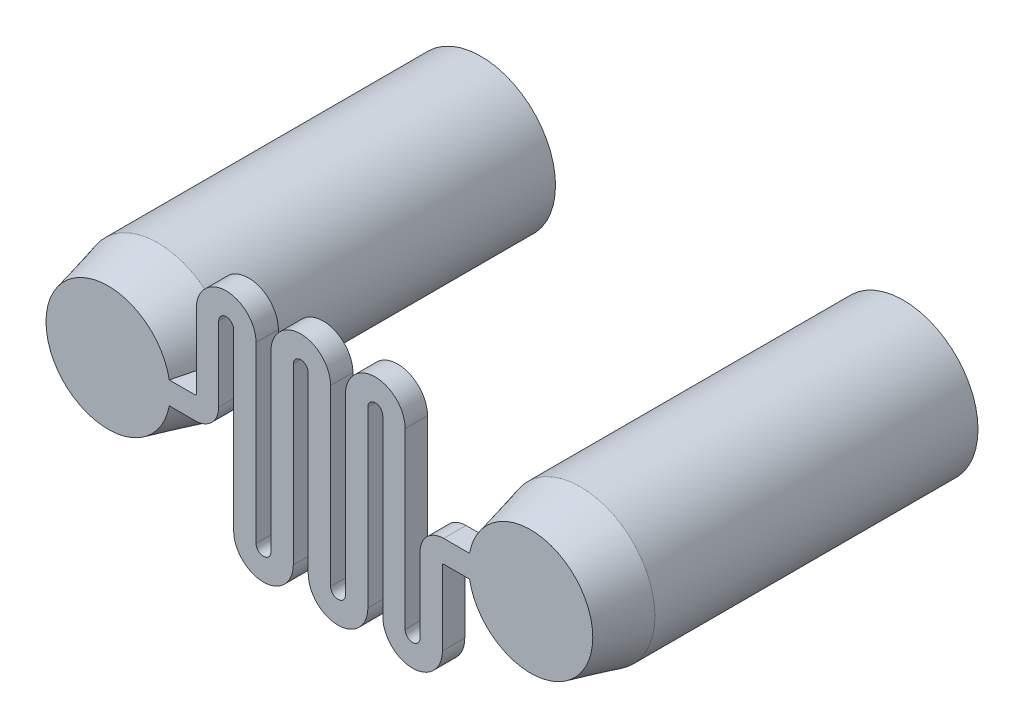
SolidWorks part; units mm, degrees
ref_plane "Front Plane" through (0, 0, 0) normal (0, 0, 1) x (1, 0, 0)
ref_plane "Top Plane" through (0, 0, 0) normal (0, 1, 0) x (1, 0, 0)
ref_plane "Right Plane" through (0, 0, 0) normal (1, 0, 0) x (0, 0, -1)
sketch "Sketch2" plane through (0, 0, 0) normal (0, 0, 1) x (1, 0, 0)
  line L3 (-20.5, -0.9) -> (-13.5, -0.9)
  line L6 (-11.6, 1) -> (-11.6, 7)
  line L9 (-10.4, 7) -> (-10.4, 0)
  line L12 (-10.4, 0) -> (-10.4, -7)
  line L15 (-5.6, -7) -> (-5.6, 0)
  line L18 (-5.6, 0) -> (-5.6, 7)
  line L21 (-4.4, 7) -> (-4.4, 0)
  line L22 (-4.4, 0) -> (-4.4, -7)
  line L23 (0.4, -7) -> (0.4, 0)
  line L24 (0.4, 0) -> (0.4, 7)
  line L25 (1.6, 7) -> (1.6, 0)
  line L26 (1.6, 0) -> (1.6, -7)
  line L27 (6.4, -7) -> (6.4, -1)
  line L28 (6.5, -0.9) -> (13.5, -0.9)
  line L29 (-20.5, 0.9) -> (-13.5, 0.9)
  line L30 (-13.4, 1) -> (-13.4, 7)
  line L31 (-8.6, 7) -> (-8.6, 0)
  line L32 (-8.6, 0) -> (-8.6, -7)
  line L33 (-7.4, -7) -> (-7.4, 0)
  line L34 (-7.4, 0) -> (-7.4, 7)
  line L35 (-2.6, 7) -> (-2.6, 0)
  line L36 (-2.6, 0) -> (-2.6, -7)
  line L37 (-1.4, -7) -> (-1.4, 0)
  line L38 (-1.4, 0) -> (-1.4, 7)
  line L39 (3.4, 7) -> (3.4, 0)
  line L40 (3.4, 0) -> (3.4, -7)
  line L41 (4.6, -7) -> (4.6, -1)
  line L42 (6.5, 0.9) -> (13.5, 0.9)
  arc A8 (-11.6, 1) -> (-13.5, -0.9) centre (-13.5, 1) cw
  arc A9 (-11.6, 7) -> (-10.4, 7) centre (-11, 7) cw
  arc A10 (-10.4, -7) -> (-5.6, -7) centre (-8, -7) ccw
  arc A11 (-5.6, 7) -> (-4.4, 7) centre (-5, 7) cw
  arc A12 (-4.4, -7) -> (0.4, -7) centre (-2, -7) ccw
  arc A13 (0.4, 7) -> (1.6, 7) centre (1, 7) cw
  arc A14 (1.6, -7) -> (6.4, -7) centre (4, -7) ccw
  arc A15 (6.4, -1) -> (6.5, -0.9) centre (6.5, -1) cw
  arc A16 (-13.4, 1) -> (-13.5, 0.9) centre (-13.5, 1) cw
  arc A17 (-13.4, 7) -> (-8.6, 7) centre (-11, 7) cw
  arc A18 (-8.6, -7) -> (-7.4, -7) centre (-8, -7) ccw
  arc A19 (-7.4, 7) -> (-2.6, 7) centre (-5, 7) cw
  arc A20 (-2.6, -7) -> (-1.4, -7) centre (-2, -7) ccw
  arc A21 (-1.4, 7) -> (3.4, 7) centre (1, 7) cw
  arc A22 (3.4, -7) -> (4.6, -7) centre (4, -7) ccw
  arc A23 (4.6, -1) -> (6.5, 0.9) centre (6.5, -1) cw
  arc A24 (-20.5, 0.9) -> (-20.5, -0.9) centre (-20.5, 0) ccw
  arc A25 (13.5, -0.9) -> (13.5, 0.9) centre (13.5, 0) ccw
  point P4 (0, 0)
  point P32 (5.5, 0)
  point P35 (-12.5, 0)
  dimension "D1" = 8
  dimension "D14" = 8
extrude "Boss-Extrude1" add sketch "Sketch2" along normal blind 1.8
ref_plane "Plane1" through (0, 0, 0) normal (0, 1, 0) x (1, 0, 0)
ref_plane "Plane2" through (0, 0, 0) normal (0, 1, 0) x (1, 0, 0)
sketch "Sketch3" plane through (0, 0, 0) normal (0, 1, 0) x (1, 0, 0)
  line L0 (-20.5, -1.8) -> (-25.5, -1.8)
  line L2 (-20.5, -1.8) -> (-20.5, 28.2)
  line L3 (-20.5, 28.2) -> (-26.5, 28.2)
  line L4 (-26.5, 28.2) -> (-26.5, 2.2)
  line L5 (-26.5, 2.2) -> (-25.5, -1.8)
  dimension "D1" = 5
  dimension "D2" = 6
  dimension "D4" = 30
revolve "Revolve1" add sketch "Sketch3" angle 360 about L2
sketch "Sketch4" plane through (0, 0, 0) normal (0, 1, 0) x (1, 0, 0)
  line L0 (13.5, -1.8) -> (18.5, -1.8)
  line L2 (13.5, -1.8) -> (13.5, 28.2)
  line L3 (13.5, 28.2) -> (19.5, 28.2)
  line L4 (19.5, 28.2) -> (19.5, 2.2)
  line L5 (19.5, 2.2) -> (18.5, -1.8)
  dimension "D1" = 5
  dimension "D3" = 6
  dimension "D4" = 30
revolve "Revolve2" add sketch "Sketch4" angle 360 about L2
sketch "Sketch5" plane through (0, 0, -28.2) normal (0, 0, -1) x (-1, 0, 0)
  circle A0 centre (-13.5, 0) radius 5
  circle A1 centre (20.5, 0) radius 5
  dimension "D1" = 10
  dimension "D2" = 10
extrude "Cut-Extrude1" cut sketch "Sketch5" against normal blind 28
